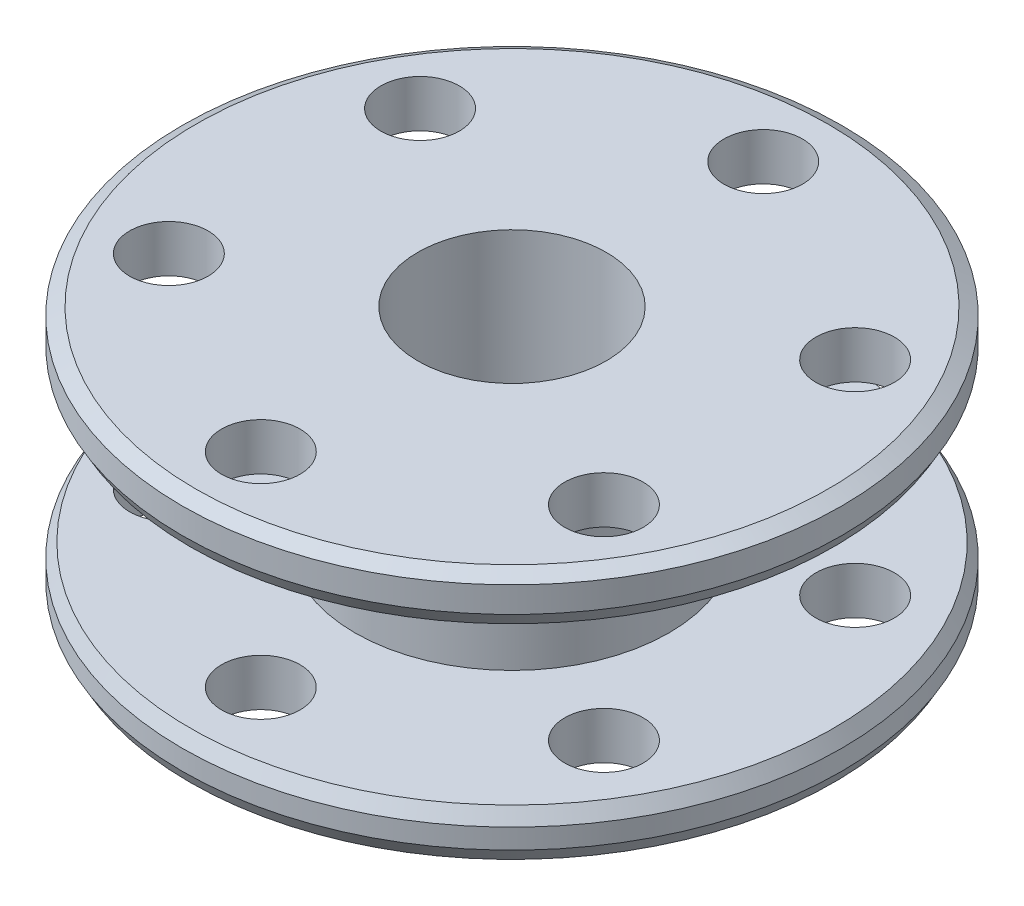
SolidWorks part; units mm, degrees
material "AISI 4340 Steel, normalized"
ref_plane "Front Plane" through (0, 0, 0) normal (0, 0, 1) x (1, 0, 0)
ref_plane "Top Plane" through (0, 0, 0) normal (0, 1, 0) x (1, 0, 0)
ref_plane "Right Plane" through (0, 0, 0) normal (1, 0, 0) x (0, 0, -1)
sketch "Sketch1" plane through (0, 0, 0) normal (0, 1, 0) x (1, 0, 0)
  circle A0 centre (0, 0) radius 21
  circle A1 centre (0, 0) radius 6
  circle A2 centre (0, 0) radius 16 construction
  circle A3 centre (0, 16) radius 2.5
  circle A4 centre (13.8564, 8) radius 2.5
  circle A5 centre (13.8564, -8) radius 2.5
  circle A6 centre (0, -16) radius 2.5
  circle A7 centre (-13.8564, -8) radius 2.5
  circle A8 centre (-13.8564, 8) radius 2.5
  point P20 (0, 0)
  dimension "D1" = 42
  dimension "D2" = 12
  dimension "D3" = 32
  dimension "D4" = 5
  dimension "D5" = 6
extrude "Boss-Extrude1" add sketch "Sketch1" along normal blind 16
sketch "Sketch2" plane through (0, 0, 0) normal (1, 0, 0) x (0, 0, -1)
  line L0 (0, 0) -> (0, 18.704) construction
  line L1 (18.5, 16) -> (13.5, 16) construction
  line L2 (10, 13) -> (32.4515, 13)
  line L3 (10, 13) -> (10, 3)
  line L4 (10, 3) -> (32.4515, 3)
  line L5 (32.4515, 13) -> (32.4515, 3)
  line L6 (-21, 0) -> (21, 0) construction
  dimension "D1" = 3
  dimension "D2" = 3
  dimension "D3" = 10
revolve "Cut-Revolve1" cut sketch "Sketch2" angle 360 about L0
chamfer "Chamfer1" distance 0.5 angle 60 4 edges at (0, 0, 21) (0, 3, -21) (0, 16, 21) (0, 13, 21)
sketch "Sketch3" plane through (0, 0, 0) normal (0, -1, 0) x (1, 0, 0)
  line L0 (0, 0) -> (0, 22.9309)
  point P3 (0, 0)
